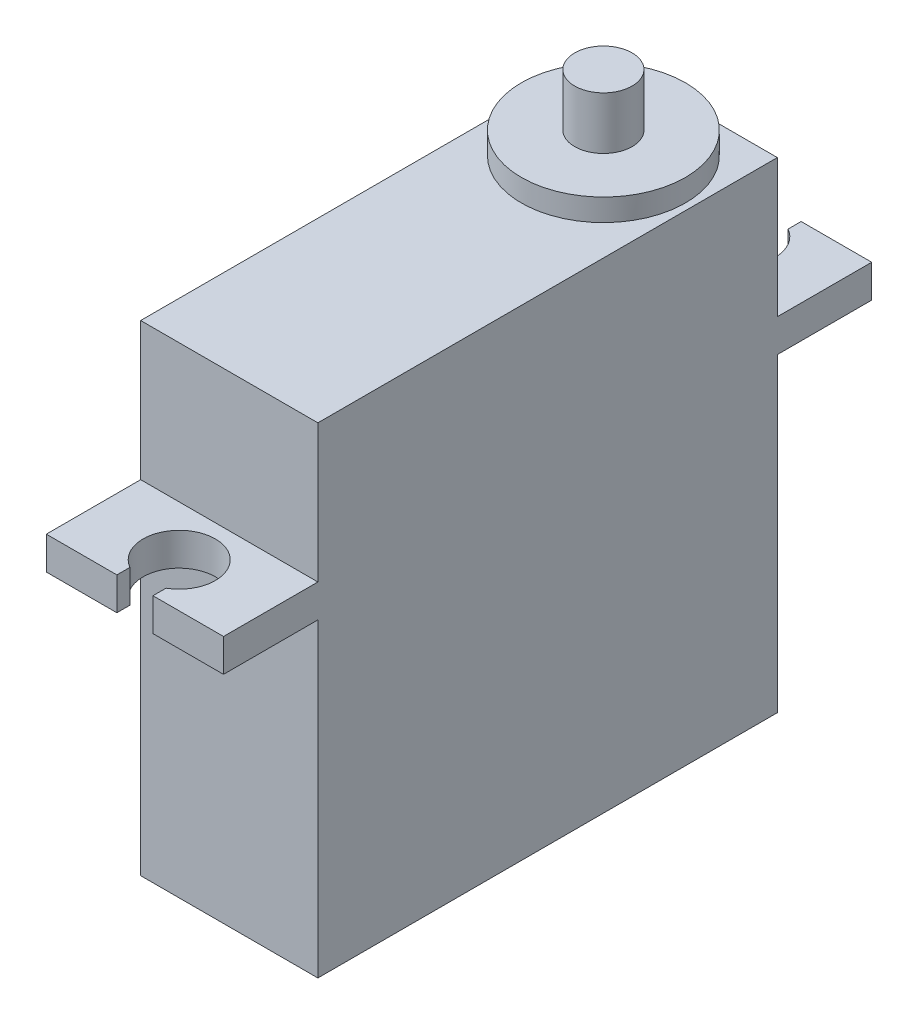
SolidWorks part; units mm, degrees
ref_plane "Front Plane" through (0, 0, 0) normal (0, 0, 1) x (1, 0, 0)
ref_plane "Top Plane" through (0, 0, 0) normal (0, 1, 0) x (1, 0, 0)
ref_plane "Right Plane" through (0, 0, 0) normal (1, 0, 0) x (0, 0, -1)
sketch "Sketch1" plane through (0, 0, 0) normal (0, 1, 0) x (1, 0, 0)
  line L1 (0, 0) -> (10.8, 0)
  line L2 (0, 0) -> (0, 28)
  line L3 (0, 28) -> (10.8, 28)
  line L4 (10.8, 0) -> (10.8, 28)
  dimension "D1" = 10.8
  dimension "D2" = 28
extrude "Boss-Extrude1" add sketch "Sketch1" along normal blind 29.3
ref_plane "Plane1" through (0, 20.9, 0) normal (0, 1, 0) x (1, 0, 0)
sketch "Sketch2" plane through (0, 20.9, 0) normal (0, 1, 0) x (1, 0, 0)
  line L0 (0, 14) -> (10.8, 14) construction
  line L1 (0, 28) -> (10.8, 28)
  line L2 (0, 28) -> (0, 33.75)
  line L3 (0, 33.75) -> (4.3, 33.75)
  line L4 (10.8, 28) -> (10.8, 33.75)
  line L5 (0, 28) -> (0, 0) construction
  line L6 (10.8, 0) -> (10.8, 28) construction
  line L7 (5.4, 33.75) -> (5.4, 28) construction
  line L8 (5.4, -5.75) -> (5.4, 0) construction
  line L9 (10.8, 0) -> (10.8, -5.75)
  line L10 (0, 0) -> (0, -5.75)
  line L11 (0, 0) -> (10.8, 0)
  line L12 (0, -5.75) -> (4.3, -5.75)
  line L13 (4.3, 33.75) -> (4.3, 32.9553)
  line L14 (6.5, 33.75) -> (6.5, 32.9553)
  line L15 (6.5, -5.75) -> (6.5, -4.9553)
  line L16 (4.3, -5.75) -> (4.3, -4.9553)
  line L17 (6.5, 33.75) -> (10.8, 33.75)
  line L18 (6.5, -5.75) -> (10.8, -5.75)
  arc A0 (4.3, 32.9553) -> (6.5, 32.9553) centre (5.4, 31.05) ccw
  arc A1 (4.3, -4.9553) -> (6.5, -4.9553) centre (5.4, -3.05) cw
  dimension "D3" = 4.4
  dimension "D1" = 39.5
  dimension "D2" = 34.1
  dimension "D4" = 2.2
extrude "Boss-Extrude2" add sketch "Sketch2" against normal blind 2
sketch "Sketch3" plane through (0, 29.3, 0) normal (0, 1, 0) x (1, 0, 0)
  line L0 (5.4, 0) -> (5.4, 28) construction
  line L1 (0, 0) -> (10.8, 0) construction
  line L2 (10.8, 28) -> (0, 28) construction
  circle A0 centre (5.4, 22.8) radius 5
  dimension "D2" = 10
  dimension "D1" = 5.2
extrude "Boss-Extrude3" add sketch "Sketch3" along normal blind 1.35
sketch "Sketch4" plane through (0, 30.65, 0) normal (0, 1, 0) x (1, 0, 0)
  circle A0 centre (5.4, 22.8) radius 1.75
  dimension "D1" = 3.5
extrude "Boss-Extrude4" add sketch "Sketch4" along normal blind 3.2
